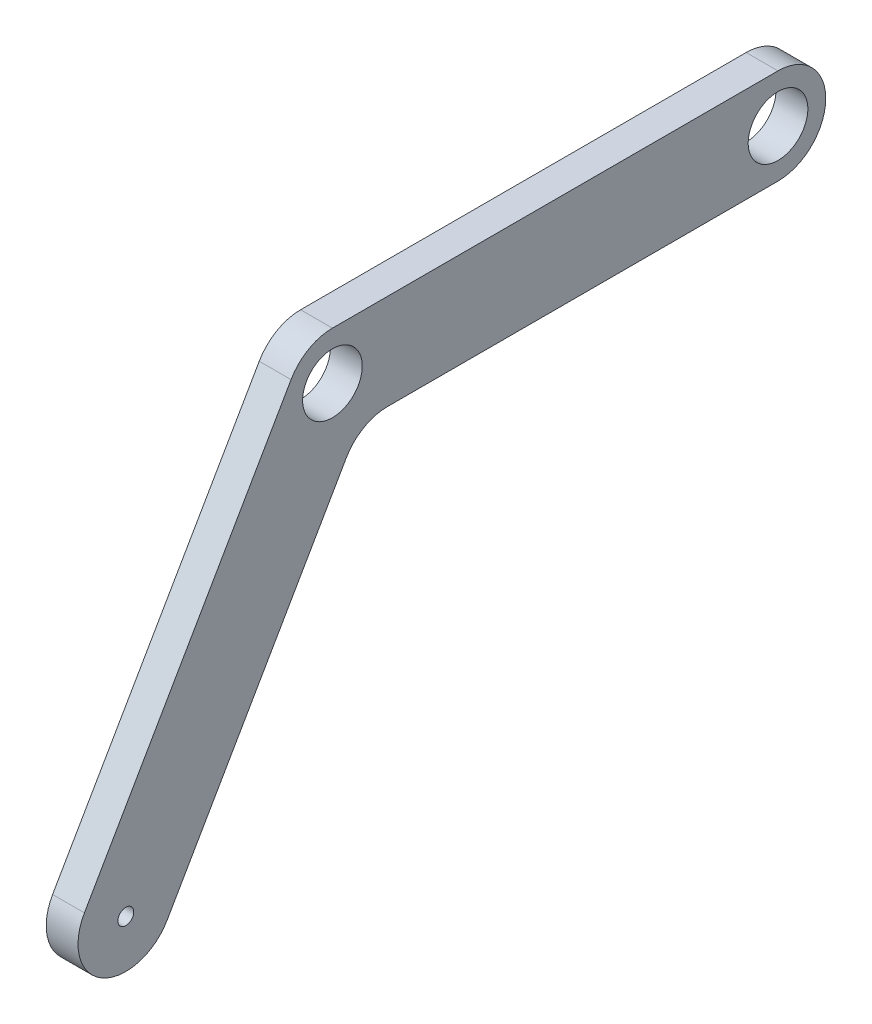
SolidWorks part; units mm, degrees
ref_plane "Front Plane" through (0, 0, 0) normal (0, 0, 1) x (1, 0, 0)
ref_plane "Top Plane" through (0, 0, 0) normal (0, 1, 0) x (1, 0, 0)
ref_plane "Right Plane" through (0, 0, 0) normal (1, 0, 0) x (0, 0, -1)
sketch "Sketch1" plane through (0, 0, 0) normal (-1, 0, 0) x (0, 0, 1)
  line L0 (0, 0) -> (-700, 0) construction
  line L1 (-86.6717, -75) -> (-700, -75)
  line L2 (0, 75) -> (-700, 75)
  line L3 (0, 0) -> (324.6107, -563.1411) construction
  line L4 (64.9778, 37.4551) -> (389.5885, -525.686)
  line L5 (-21.6939, -112.5449) -> (259.6328, -600.5962)
  arc A0 (-21.6939, -112.5449) -> (-86.6717, -75) centre (-86.6717, -150) ccw
  arc A1 (-700, 75) -> (-700, -75) centre (-700, 0) ccw
  arc A2 (64.9778, 37.4551) -> (0, 75) centre (0, 0) ccw
  arc A3 (259.6328, -600.5962) -> (389.5885, -525.686) centre (324.6107, -563.1411) ccw
  circle A4 centre (-700, 0) radius 46.875
  circle A5 centre (0, 0) radius 46.875
  circle A6 centre (324.6107, -563.1411) radius 12.5
  point P3 (-350, 0)
  point P8 (162.3053, -281.5706)
  dimension "D1" = 75
  dimension "D2" = 650
  dimension "D6" = 93.75
  dimension "D7" = 25
  dimension "D8" = 75
  dimension "D3" = 700
extrude "Boss-Extrude1" add sketch "Sketch1" along normal blind 50
